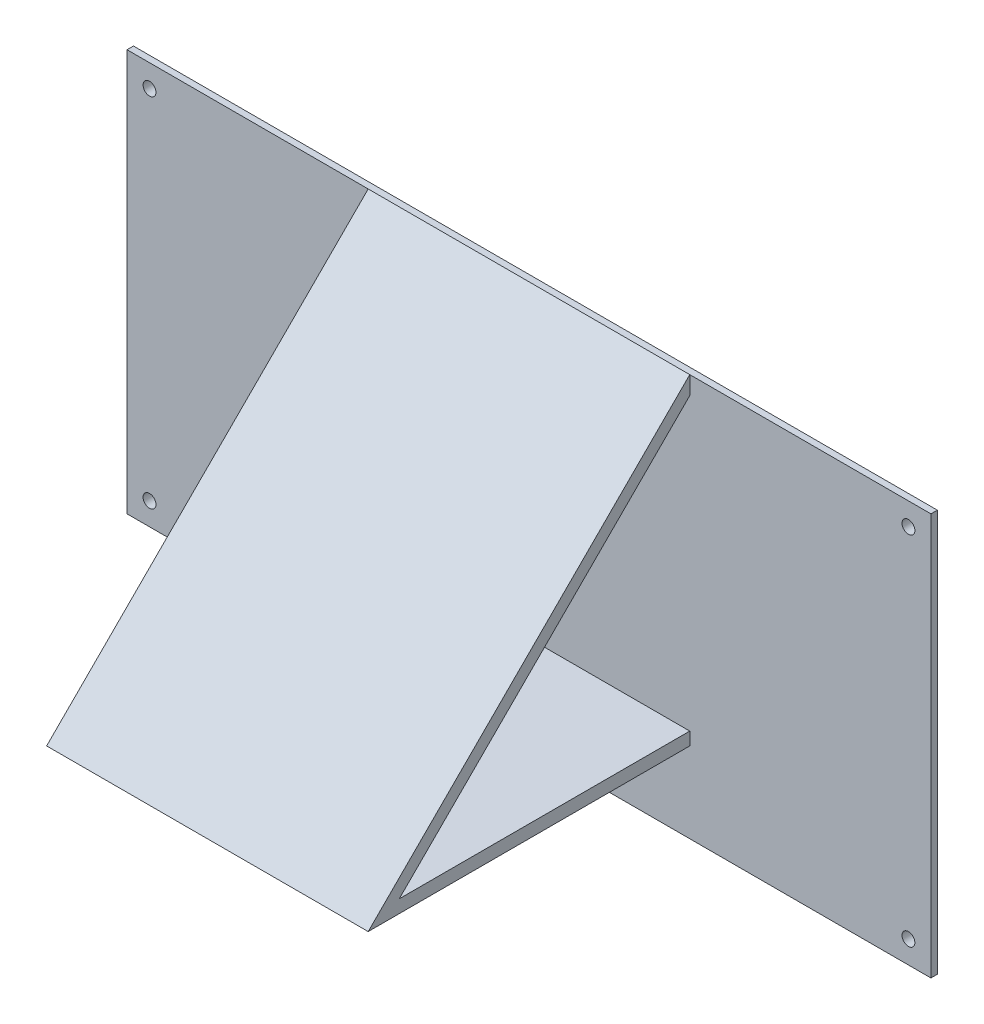
SolidWorks part; units mm, degrees
ref_plane "Ebene vorne" through (0, 0, 0) normal (0, 0, 1) x (1, 0, 0)
ref_plane "Ebene oben" through (0, 0, 0) normal (0, 1, 0) x (1, 0, 0)
ref_plane "Ebene rechts" through (0, 0, 0) normal (1, 0, 0) x (0, 0, -1)
sketch "Skizze1" plane through (0, 0, 0) normal (0, 0, 1) x (1, 0, 0)
  line L1 (0, 125) -> (250, 125)
  line L2 (0, 125) -> (0, 0)
  line L3 (0, 0) -> (250, 0)
  line L4 (250, 125) -> (250, 0)
  dimension "D1" = 250
  dimension "D2" = 125
extrude "Aufsatz-Linear austragen1" add sketch "Skizze1" along normal blind 2 contours L2 L1 L4 L3
sketch "Skizze2" plane through (0, 0, 2) normal (0, 0, 1) x (1, 0, 0)
  line L0 (75, 75) -> (0, 75) construction
  line L1 (75, 125) -> (175, 125)
  line L2 (75, 125) -> (75, 25)
  line L3 (75, 25) -> (175, 25)
  line L4 (175, 125) -> (175, 25)
  line L5 (0, 125) -> (0, 0) construction
  line L6 (175, 75) -> (250, 75) construction
  line L7 (250, 125) -> (250, 0) construction
  line L8 (0, 125) -> (250, 125) construction
  dimension "D1" = 100
  dimension "D2" = 100
extrude "Aufsatz-Linear austragen2" add sketch "Skizze2" along normal blind 100
sketch "Skizze3" plane through (75, 0, 0) normal (-1, 0, 0) x (0, 0, 1)
  line L0 (102, 25) -> (102, 125)
  line L1 (102, 125) -> (2, 125)
  line L2 (2, 125) -> (102, 25)
extrude "Schnitt-Linear austragen1" cut sketch "Skizze3" against normal blind 100
sketch "Skizze4" plane through (75, 0, 0) normal (-1, 0, 0) x (0, 0, 1)
  line L0 (2, 119.3431) -> (92.3431, 29)
  line L1 (92.3431, 29) -> (2, 29)
  line L2 (2, 29) -> (2, 119.3431)
  line L3 (2, 125) -> (102, 25) construction
  line L5 (102, 25) -> (2, 25) construction
  line L6 (2, 125) -> (2, 25) construction
  dimension "D1" = 4
  dimension "D3" = 4
extrude "Schnitt-Linear austragen2" cut sketch "Skizze4" against normal blind 100 contours L2 L0 L1
sketch "Skizze6" plane through (0, 0, 0) normal (0, 0, -1) x (-1, 0, 0)
  line L0 (0, 125) -> (-250, 125) construction
  line L1 (-246, 121) -> (-4, 121)
  line L2 (-246, 121) -> (-246, 4)
  line L3 (-246, 4) -> (-4, 4)
  line L4 (-4, 121) -> (-4, 4)
  line L5 (-250, 125) -> (-250, 0) construction
  line L6 (0, 0) -> (-250, 0) construction
  line L7 (0, 125) -> (0, 0) construction
  dimension "D1" = 4
  dimension "D2" = 4
  dimension "D3" = 4
  dimension "D4" = 4
extrude "Aufsatz-Linear austragen3" add sketch "Skizze6" along normal blind 2
sketch "Skizze7" plane through (0, 0, -2) normal (0, 0, -1) x (-1, 0, 0)
  line L0 (-4, 121) -> (-246, 121) construction
  line L1 (-246, 121) -> (-246, 4) construction
  line L2 (-246, 4) -> (-4, 4) construction
  line L3 (-4, 4) -> (-4, 121) construction
  line L4 (-246, 4) -> (-4, 4) construction
  line L5 (-4, 4) -> (-4, 121) construction
  circle A0 centre (-243, 118) radius 2
  circle A1 centre (-7, 7) radius 2
  circle A2 centre (-7, 118) radius 2
  circle A3 centre (-243, 7) radius 2
  point P2 (0, 0)
  dimension "D1" = 3
  dimension "D2" = 3
  dimension "D3" = 3
  dimension "D4" = 3
  dimension "D5" = 3
  dimension "D6" = 3
  dimension "D7" = 3
  dimension "D8" = 3
extrude "Schnitt-Linear austragen5" cut sketch "Skizze7" against normal blind 32
